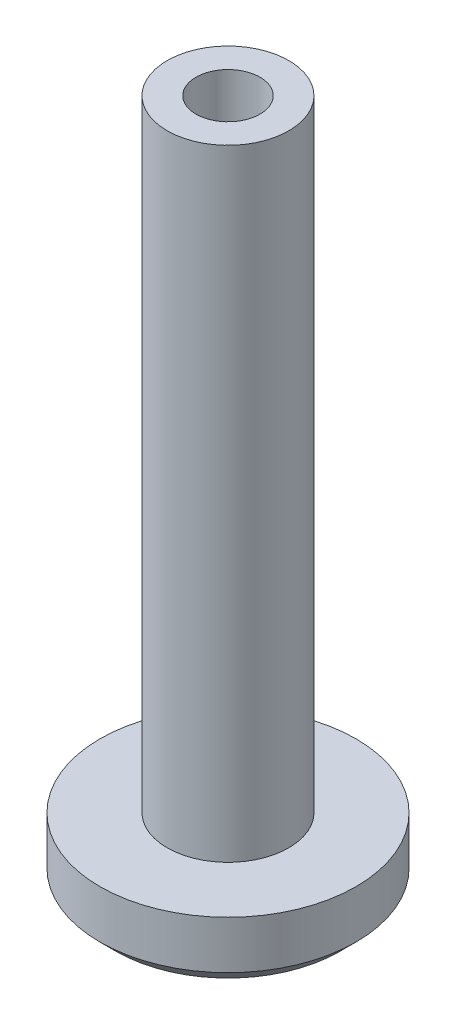
SolidWorks part; units mm, degrees
material "1023 Carbon Steel Sheet (SS)"
ref_plane "Front Plane" through (0, 0, 0) normal (0, 0, 1) x (1, 0, 0)
ref_plane "Top Plane" through (0, 0, 0) normal (0, 1, 0) x (1, 0, 0)
ref_plane "Right Plane" through (0, 0, 0) normal (1, 0, 0) x (0, 0, -1)
sketch "Sketch1" plane through (0, 0, 0) normal (0, 1, 0) x (1, 0, 0)
  circle A0 centre (0, 0) radius 1.9
  dimension "D1" = 3.8
extrude "Boss-Extrude1" add sketch "Sketch1" along normal blind 19.4
sketch "Sketch2" plane through (0, 0, 0) normal (0, -1, 0) x (1, 0, 0)
  circle A0 centre (0, 0) radius 4
  dimension "D1" = 8
extrude "Boss-Extrude2" add sketch "Sketch2" along normal blind 2
chamfer "Chamfer1" distance 0.5 angle 45 1 edges at (0, -2, -4)
sketch "Sketch3" plane through (0, 19.4, 0) normal (0, 1, 0) x (1, 0, 0)
  circle A0 centre (0, 0) radius 1
  dimension "D1" = 2
extrude "Cut-Extrude1" cut sketch "Sketch3" against normal blind 3
